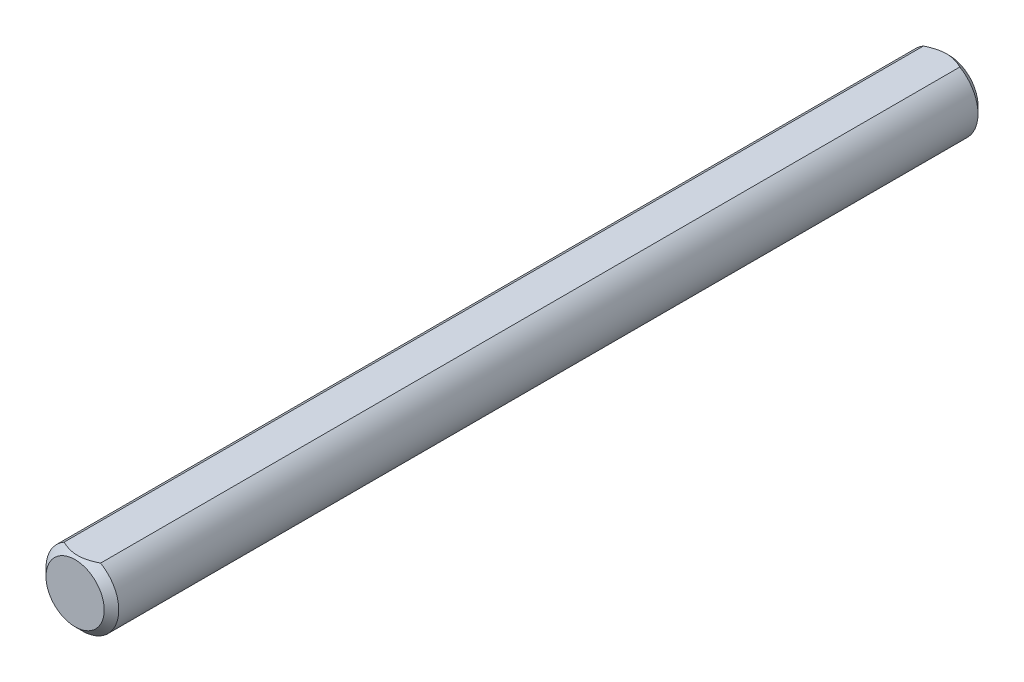
SolidWorks part; units mm, degrees
ref_plane "Front" through (0, 0, 0) normal (0, 0, 1) x (1, 0, 0)
ref_plane "Top" through (0, 0, 0) normal (0, 1, 0) x (1, 0, 0)
ref_plane "Right" through (0, 0, 0) normal (1, 0, 0) x (0, 0, -1)
sketch "Sketch1" plane through (0, 0, 0) normal (0, 0, 1) x (1, 0, 0)
  circle A0 centre (0, 0) radius 3.175
  dimension "D1" = 6.35
extrude "Extrude1" add sketch "Sketch1" along normal mid plane 76.2
chamfer "Chamfer1" distance 0.635 angle 45 2 edges at (3.175, 0, -38.1) (3.175, 0, 38.1)
sketch "Sketch13" plane through (0, 0, 0) normal (0, 0, 1) x (1, 0, 0)
  line L3 (-1.5875, 2.7496) -> (1.5875, 2.7496)
  circle A0 centre (0, 0) radius 3.175 construction
  arc A1 (1.5875, 2.7496) -> (-1.5875, 2.7496) centre (0, 0) ccw
  dimension "D1" = 3.175
extrude "Extrude7" cut sketch "Sketch13" against normal through all and the other way through all
equation "\"D1@Chamfer1\" = \"D1@Sketch1\" * .1"
equation "\"D1@Sketch13\" = \"D1@Sketch1\" * .5"
